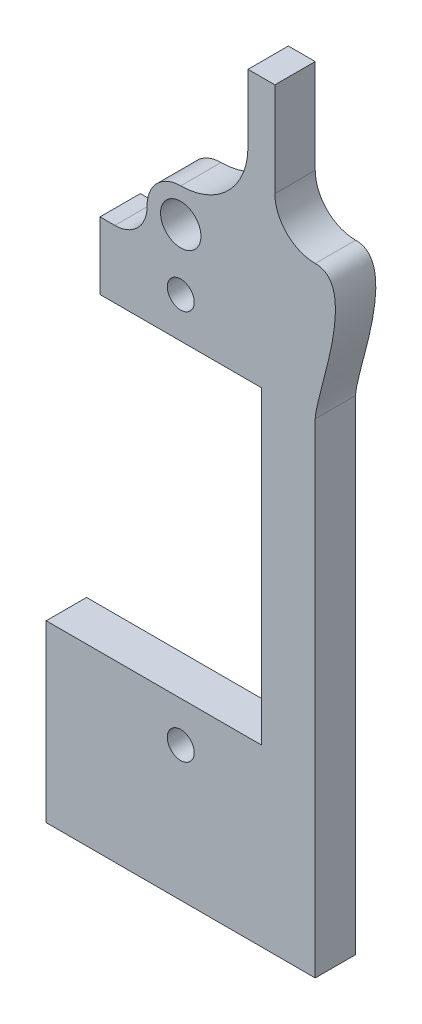
SolidWorks part; units mm, degrees
ref_plane "Alzado" through (0, 0, 0) normal (0, 0, 1) x (1, 0, 0)
ref_plane "Planta" through (0, 0, 0) normal (0, 1, 0) x (1, 0, 0)
ref_plane "Vista lateral" through (0, 0, 0) normal (1, 0, 0) x (0, 0, -1)
sketch "Croquis2" plane through (0, 0, 0) normal (0, 0, 1) x (1, 0, 0)
  line L0 (-10, 0) -> (10, 0) construction
  line L1 (10, 0) -> (10, 30)
  line L2 (10, 50) -> (-10, 50) construction
  line L3 (-10, 50) -> (-10, 0) construction
  line L4 (0, 50) -> (0, 40) construction
  line L5 (-10, 25) -> (-5, 25) construction
  line L6 (-5, 25) -> (-5, 45) construction
  line L7 (5, 45) -> (5, 50) construction
  line L8 (0, 40) -> (-5, 40) construction
  line L9 (0, 0) -> (0, 2) construction
  line L10 (6, 30) -> (6, 7) construction
  line L11 (6, 7) -> (-6, 7) construction
  line L12 (-6, 7) -> (-6, 30) construction
  line L13 (-6, 30) -> (6, 30) construction
  line L14 (-6, 35) -> (-4.9, 35)
  line L15 (0, 2) -> (0, 4) construction
  line L16 (0, 4) -> (0, 7) construction
  line L17 (-10, 0) -> (-10, 7)
  line L19 (0, 30) -> (0, 33) construction
  line L20 (5, 45) -> (5, 50)
  line L21 (-2.5, 37.4) -> (-2.5, 37.5)
  line L22 (5, 50) -> (7, 50)
  line L23 (-6, 35) -> (-6, 30) construction
  line L24 (-6, 35) -> (-6, 30)
  line L25 (7, 50) -> (7, 43)
  line L26 (-6, 30) -> (6, 30)
  line L27 (6, 30) -> (6, 7)
  line L28 (6, 7) -> (-10, 7)
  line L29 (0, 24) -> (-10.5, 24) construction
  line L30 (0, 30) -> (0, 24) construction
  line L31 (0, 40) -> (10.5, 40) construction
  line L34 (-10, 0) -> (-10, -6)
  line L35 (-10, -6) -> (10, -6)
  line L36 (10, 0) -> (10, -6)
  arc A0 (0, 40) -> (5, 45) centre (0, 45) ccw
  circle A1 centre (0, 37.5) radius 1.5
  arc A2 (0, 40) -> (-2.5, 37.5) centre (0, 37.5) ccw
  arc A3 (7, 43) -> (10, 40) centre (10, 43) ccw
  circle A4 centre (0, 33) radius 1
  circle A5 centre (0, 4) radius 1
  arc A6 (-4.9, 35) -> (-2.5, 37.4) centre (-4.9, 37.4) ccw
  circle A7 centre (0, 45) radius 5 construction
  spline S0 degree 3 poles (10, 40) (13.3825, 40) (10, 31.6044) (10, 30) knots 0 0 0 0 1 1 1 1
  dimension "D3" = 2.4
  dimension "D1" = 50
  dimension "D2" = 20
  dimension "D4" = 6
  dimension "D5" = 13.5
extrude "Saliente-Extruir1" add sketch "Croquis2" along normal blind 3
